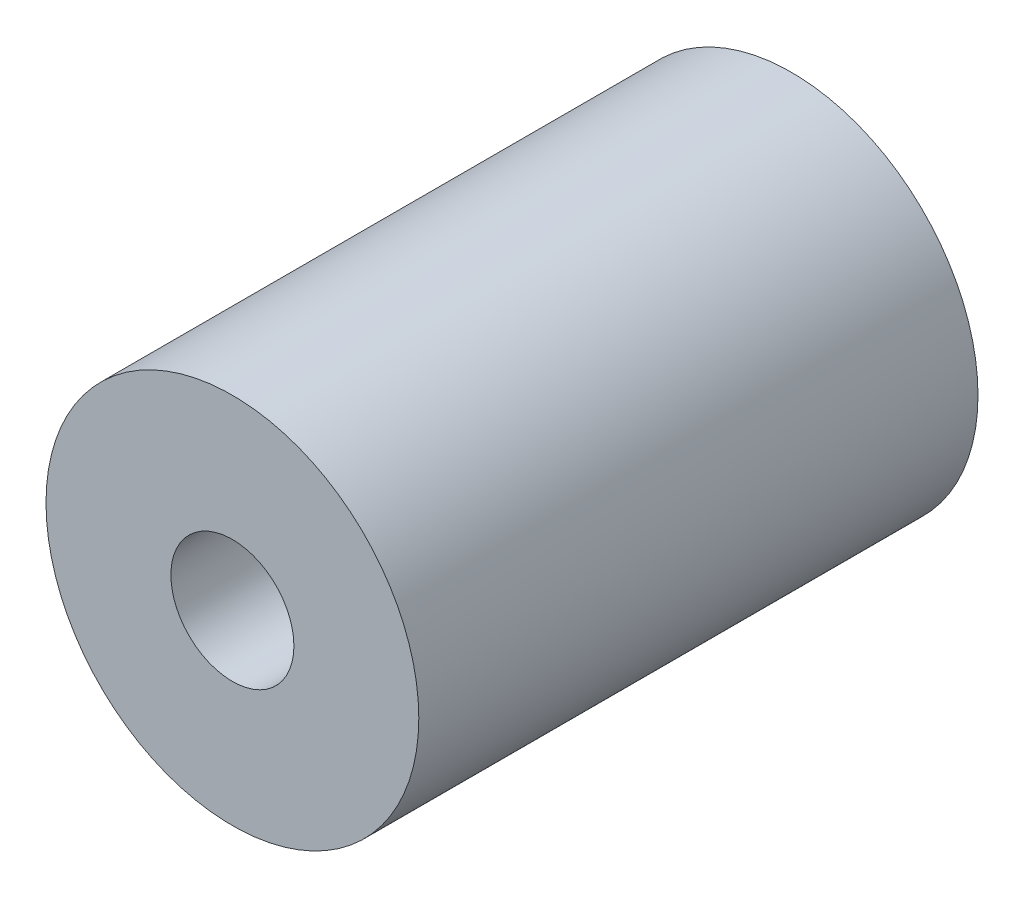
SolidWorks part; units mm, degrees
material "5052-H34"
ref_plane "正面" through (0, 0, 0) normal (0, 0, 1) x (1, 0, 0)
ref_plane "平面" through (0, 0, 0) normal (0, 1, 0) x (1, 0, 0)
ref_plane "右側面" through (0, 0, 0) normal (1, 0, 0) x (0, 0, -1)
sketch "ｽｹｯﾁ1" plane through (0, 0, 0) normal (0, 0, 1) x (1, 0, 0)
  circle A0 centre (0, 0) radius 1.65
  circle A1 centre (0, 0) radius 5
  dimension "D1" = 10
  dimension "D2" = 3.3
extrude "ﾎﾞｽ - 押し出し1" add sketch "ｽｹｯﾁ1" along normal blind 15
